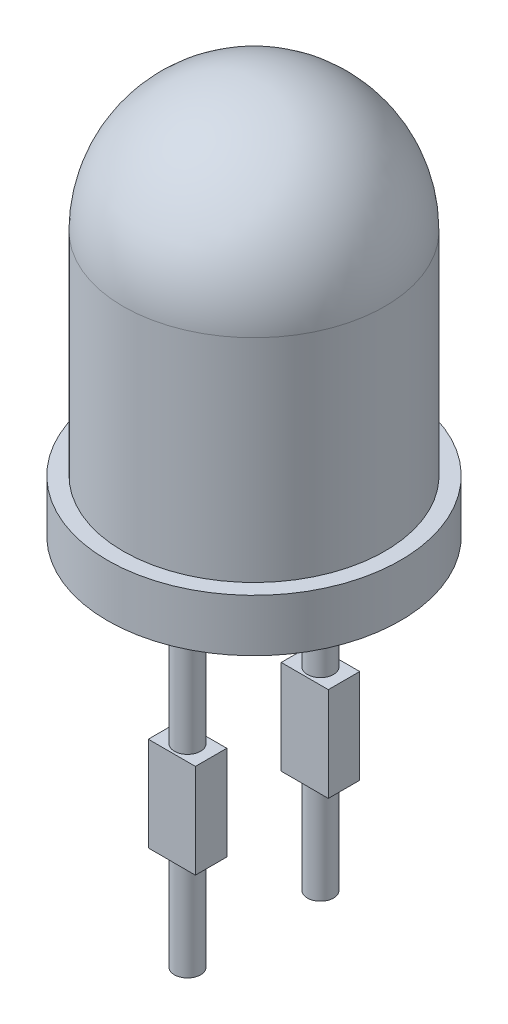
SolidWorks part; units mm, degrees
ref_plane "Front Plane" through (0, 0, 0) normal (0, 0, 1) x (1, 0, 0)
ref_plane "Top Plane" through (0, 0, 0) normal (0, 1, 0) x (1, 0, 0)
ref_plane "Right Plane" through (0, 0, 0) normal (1, 0, 0) x (0, 0, -1)
sketch "Sketch1" plane through (0, 0, 0) normal (1, 0, 0) x (0, 0, -1)
  line L0 (0, 4.525) -> (0, -10.9525) construction
  line L1 (-2.5, 2.025) -> (-2.5, -2.025)
  line L2 (-2.5, -2.025) -> (-2.8, -2.025)
  line L3 (-2.8, -2.025) -> (-2.8, -3.025)
  line L4 (-2.8, -3.025) -> (0, -3.025)
  line L5 (0, 4.525) -> (-4.2269, 4.525) construction
  line L6 (0, 4.525) -> (0, -3.025)
  arc A0 (-2.5, 2.025) -> (0, 4.525) centre (0, 2.025) cw
  point P11 (-2.5, 0)
  dimension "D1" = 5
  dimension "D2" = 7.55
  dimension "D3" = 1
  dimension "D4" = 5.6
revolve "Revolve1" add sketch "Sketch1" angle 360 about L0
sketch "Sketch2" plane through (0, -3.025, 0) normal (0, -1, 0) x (1, 0, 0)
  line L0 (0, 0) -> (3.908, 0) construction
  circle A0 centre (0, 1.27) radius 0.25
  circle A1 centre (0, -1.27) radius 0.25
  dimension "D1" = 2.54
  dimension "D2" = 0.5
extrude "Boss-Extrude1" add sketch "Sketch2" along normal blind 11 separate body
sketch "Sketch3" plane through (0, 0, 0) normal (1, 0, 0) x (0, 0, -1)
  line L0 (1.27, -3.025) -> (1.27, -15.6133) construction
  line L1 (0.97, -5.825) -> (1.57, -5.825)
  line L2 (0.97, -5.825) -> (0.97, -7.625)
  line L3 (0.97, -7.625) -> (1.57, -7.625)
  line L4 (1.57, -5.825) -> (1.57, -7.625)
  line L5 (0.97, -5.825) -> (1.57, -7.625) construction
  line L6 (0.97, -7.625) -> (1.57, -5.825) construction
  line L7 (1.52, -3.025) -> (1.02, -3.025) construction
  line L8 (-2.8, -3.025) -> (2.8, -3.025) construction
  line L9 (0, 0) -> (0, -3.6509) construction
  line L10 (-0.97, -7.625) -> (-1.57, -7.625)
  line L11 (-1.57, -5.825) -> (-1.57, -7.625)
  line L12 (-0.97, -5.825) -> (-1.57, -5.825)
  line L13 (-0.97, -5.825) -> (-0.97, -7.625)
  point P0 (1.27, -6.725)
  dimension "D1" = 0.6
  dimension "D2" = 2.8
  dimension "D3" = 1.8
extrude "Boss-Extrude2" add sketch "Sketch3" along normal mid plane 0.9
sketch "Sketch4" plane through (0, 0, 0) normal (1, 0, 0) x (0, 0, -1)
  line L0 (-2.8, -3.025) -> (2.8, -3.025) construction
  line L1 (-2.1452, -9.525) -> (2.8987, -9.525)
  line L2 (-2.1452, -9.525) -> (-2.1452, -15.9921)
  line L3 (-2.1452, -15.9921) -> (2.8987, -15.9921)
  line L4 (2.8987, -9.525) -> (2.8987, -15.9921)
  dimension "D1" = 5.0439
  dimension "D2" = 6.5
extrude "Cut-Extrude1" cut sketch "Sketch4" against normal through all both and the other way through all
